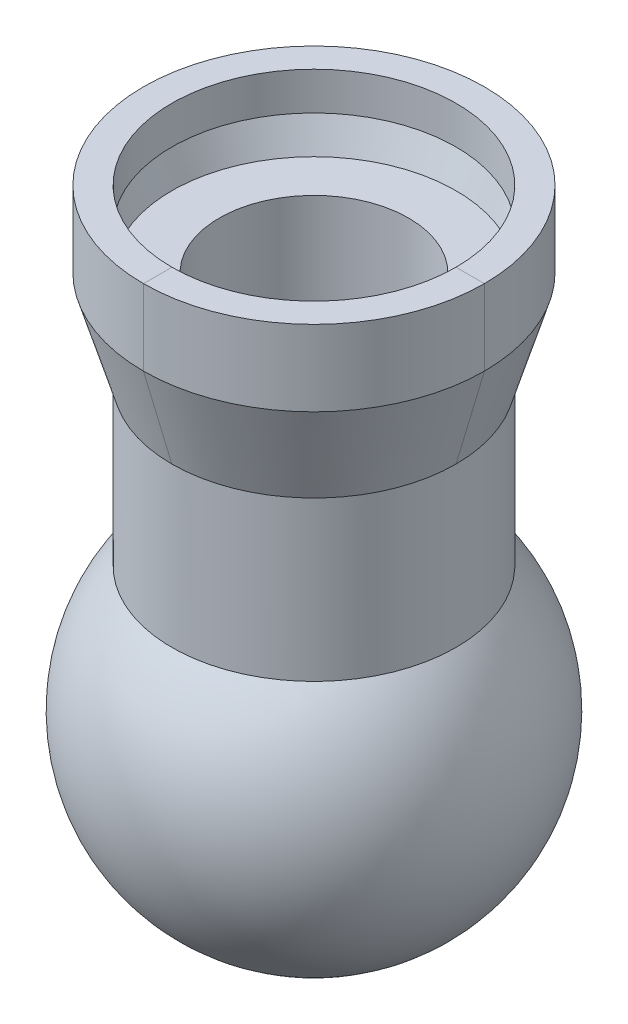
SolidWorks part; units mm, degrees
ref_plane "前视基准面" through (0, 0, 0) normal (0, 0, 1) x (1, 0, 0)
ref_plane "上视基准面" through (0, 0, 0) normal (0, 1, 0) x (1, 0, 0)
ref_plane "右视基准面" through (0, 0, 0) normal (1, 0, 0) x (0, 0, -1)
sketch "草图1" plane through (0, 0, 0) normal (0, 0, 1) x (1, 0, 0)
  line L0 (0, 10) -> (0, -10)
  arc A0 (0, -10) -> (0, 10) centre (0, 0) ccw
  dimension "D1" = 20
sketch "草图2" plane through (0, 0, 0) normal (0, 1, 0) x (1, 0, 0)
  circle A0 centre (0, 0) radius 10
  dimension "D1" = 20
sweep "扫描1" add profiles "草图1" path "草图2"
sketch "草图3" plane through (0, 0, 0) normal (0, 1, 0) x (1, 0, 0)
  circle A0 centre (0, 0) radius 7.5
  dimension "D1" = 15
extrude "凸台-拉伸1" add sketch "草图3" along normal blind 20
sketch "草图4" plane through (0, 0, 0) normal (0, 0, 1) x (1, 0, 0)
  line L0 (7.5, 20) -> (7.5, 22) construction
  line L4 (7.5, 22) -> (8.3, 22) construction
  line L5 (8.3, 22) -> (7.5, 20) construction
  line L6 (7.5, 22) -> (8.3, 22)
  line L7 (8.3, 22) -> (7.5, 20)
  line L8 (7.5, 22) -> (7.5, 24)
  line L9 (7.5, 24) -> (9, 24)
  line L10 (9, 24) -> (9, 20)
  line L11 (9, 20) -> (7.5, 20) construction
  line L12 (7.5, 20) -> (7.5, 15)
  line L13 (7.5, 6.6144) -> (7.5, 20) construction
  line L14 (7.5, 15) -> (9, 20)
  dimension "D1" = 2
  dimension "D2" = 0.8
  dimension "D3" = 2
  dimension "D4" = 1.5
  dimension "D5" = 5
sweep "扫描2" add profiles "草图4" path edge at (0, 20, 7.5)
sketch "草图5" plane through (0, 20, 0) normal (0, 1, 0) x (1, 0, 0)
  circle A0 centre (0, 0) radius 5
  dimension "D1" = 10
extrude "切除-拉伸1" cut sketch "草图5" against normal through all
